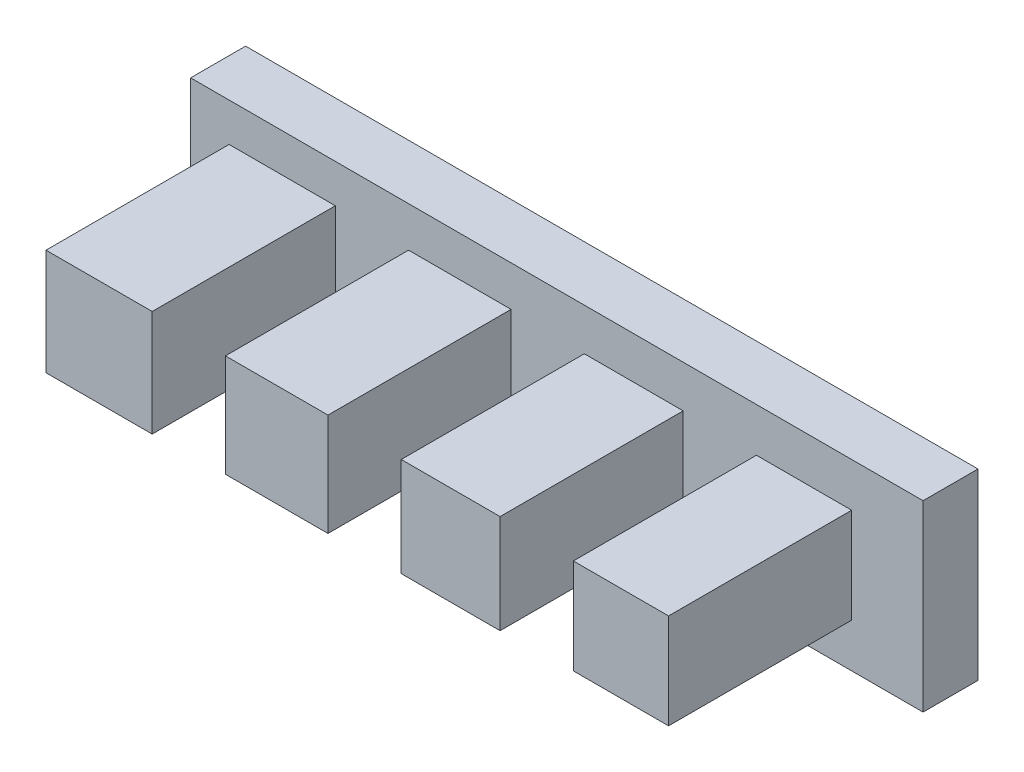
SolidWorks part; units mm, degrees
ref_plane "Front Plane" through (0, 0, 0) normal (0, 0, 1) x (1, 0, 0)
ref_plane "Top Plane" through (0, 0, 0) normal (0, 1, 0) x (1, 0, 0)
ref_plane "Right Plane" through (0, 0, 0) normal (1, 0, 0) x (0, 0, -1)
sketch "Sketch1" plane through (0, 0, 0) normal (0, 0, 1) x (1, 0, 0)
  line L1 (0, 0) -> (20, 0)
  line L2 (0, 0) -> (0, 5)
  line L3 (0, 5) -> (20, 5)
  line L4 (20, 0) -> (20, 5)
  dimension "D1" = 5
  dimension "D2" = 20
extrude "Boss-Extrude1" add sketch "Sketch1" along normal blind 1.5
sketch "Sketch2" plane through (0, 0, 1.5) normal (0, 0, 1) x (1, 0, 0)
  line L0 (0, 5) -> (0, 0) construction
  line L1 (1.05, 1.05) -> (3.95, 1.05)
  line L2 (1.05, 1.05) -> (1.05, 3.95)
  line L3 (1.05, 3.95) -> (3.95, 3.95)
  line L4 (3.95, 1.05) -> (3.95, 3.95)
  line L5 (20, 5) -> (0, 5) construction
  line L7 (5.95, 3.9) -> (8.75, 3.9)
  line L8 (5.95, 3.9) -> (5.95, 1.1)
  line L9 (5.95, 1.1) -> (8.75, 1.1)
  line L10 (8.75, 3.9) -> (8.75, 1.1)
  line L11 (10.75, 3.85) -> (13.45, 3.85)
  line L12 (10.75, 3.85) -> (10.75, 1.15)
  line L13 (10.75, 1.15) -> (13.45, 1.15)
  line L14 (13.45, 3.85) -> (13.45, 1.15)
  line L15 (15.45, 3.8) -> (18.05, 3.8)
  line L16 (15.45, 3.8) -> (15.45, 1.2)
  line L17 (15.45, 1.2) -> (18.05, 1.2)
  line L18 (18.05, 3.8) -> (18.05, 1.2)
  dimension "D1" = 2.9
  dimension "D2" = 2.9
  dimension "D3" = 1.05
  dimension "D4" = 1.05
  dimension "D5" = 2.8
  dimension "D6" = 2.8
  dimension "D7" = 1.1
  dimension "D8" = 2
  dimension "D9" = 2.7
  dimension "D10" = 2.7
  dimension "D11" = 1.15
  dimension "D12" = 2
  dimension "D13" = 2.6
  dimension "D14" = 2.6
  dimension "D15" = 2
  dimension "D16" = 1.2
extrude "Boss-Extrude2" add sketch "Sketch2" along normal blind 5
